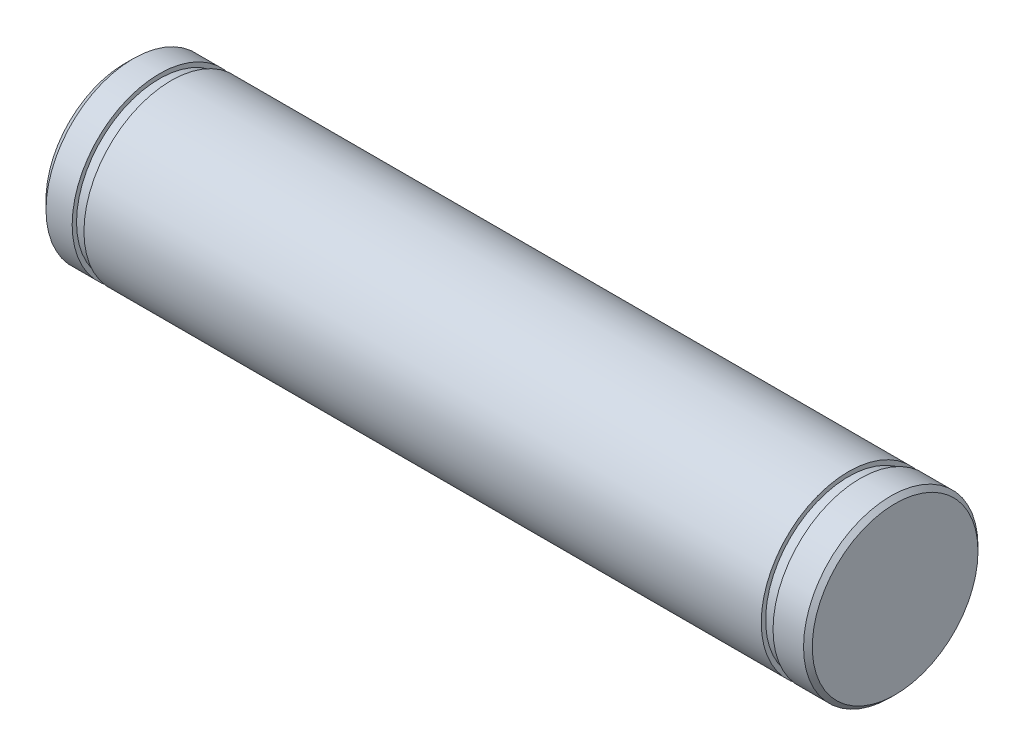
SolidWorks part; units mm, degrees
material "Stainless Steel (ferritic)"
ref_plane "Front Plane" through (0, 0, 0) normal (0, 0, 1) x (1, 0, 0)
ref_plane "Top Plane" through (0, 0, 0) normal (0, 1, 0) x (1, 0, 0)
ref_plane "Right Plane" through (0, 0, 0) normal (1, 0, 0) x (0, 0, -1)
sketch "Sketch1" plane through (0, 0, 0) normal (1, 0, 0) x (0, 0, -1)
  circle A0 centre (0, 0) radius 10
  dimension "D1" = 20
extrude "Boss-Extrude1" add sketch "Sketch1" along normal mid plane 88.35
ref_plane "Plane1" through (40.175, 0, 0) normal (1, 0, 0) x (0, 0, -1)
sketch "Sketch2" plane through (40.175, 0, 0) normal (1, 0, 0) x (0, 0, -1)
  circle A0 centre (0, 0) radius 9.5
  circle A1 centre (0, 0) radius 10
  circle A2 centre (0, 0) radius 10
  dimension "D2" = 19
  dimension "D1" = 0
extrude "Cut-Extrude1" cut sketch "Sketch2" against normal blind 1.35
chamfer "Chamfer1" distance 0.5 angle 45 1 edges at (44.175, 0, -10)
chamfer "Chamfer2" distance 1 angle 45 1 edges at (-44.175, 0, -10)
mirror "Mirror1" about plane through (0, 0, 0) normal (1, 0, 0) of "Cut-Extrude1"
sketch "Sketch3" plane through (0, 0, 0) normal (0, 1, 0) x (1, 0, 0)
  line L0 (38.825, 10) -> (-38.825, 10) construction
  line L1 (-31, -10) -> (31, -10)
  line L2 (-31, -10) -> (-31, 10)
  line L3 (-31, 10) -> (31, 10)
  line L4 (31, -10) -> (31, 10)
  line L5 (-31, -10) -> (31, 10) construction
  line L6 (-31, 10) -> (31, -10) construction
  point P0 (0, 0)
  dimension "D1" = 62
